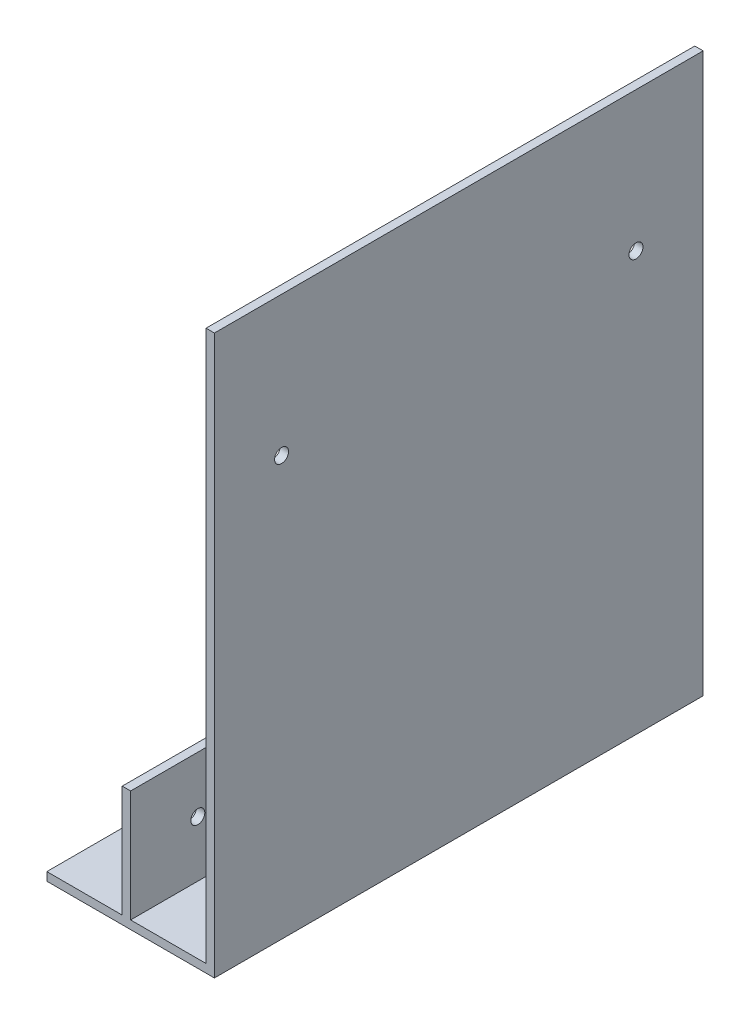
SolidWorks part; units mm, degrees
ref_plane "Front Plane" through (0, 0, 0) normal (0, 0, 1) x (1, 0, 0)
ref_plane "Top Plane" through (0, 0, 0) normal (0, 1, 0) x (1, 0, 0)
ref_plane "Right Plane" through (0, 0, 0) normal (1, 0, 0) x (0, 0, -1)
sketch "Sketch1" plane through (0, 0, 0) normal (0, 0, 1) x (1, 0, 0)
  line L0 (3, 58.977) -> (3, -21.023)
  line L1 (3, -21.023) -> (57, -21.023)
  line L3 (3, 58.977) -> (-3, 58.977)
  line L4 (57, -27.023) -> (-57, -27.023)
  line L5 (0, 78.1564) -> (0, -121.8463) construction
  line L6 (-57, -21.023) -> (-57, -27.023)
  line L7 (-3, -21.023) -> (-57, -21.023)
  line L8 (-3, 58.977) -> (-3, -21.023)
  line L9 (57, -21.023) -> (57, 372.977)
  line L10 (57, 372.977) -> (63, 372.977)
  line L11 (63, 372.977) -> (63, -27.023)
  line L12 (57, -27.023) -> (63, -27.023)
  point P10 (0, 58.977)
  point P11 (0, -27.023)
  dimension "D1" = 80
  dimension "D2" = 6
  dimension "D3" = 3
  dimension "D4" = 54
  dimension "D5" = 400
  dimension "D6" = 6
extrude "Boss-Extrude1" add sketch "Sketch1" along normal blind 350
sketch "Sketch2" plane through (0, -21.023, 0) normal (0, 1, 0) x (1, 0, 0)
  line L0 (-30, 0) -> (-30, -350) construction
  line L1 (-3, 0) -> (-57, 0) construction
  line L2 (-3, -350) -> (-57, -350) construction
  line L3 (-57, -175) -> (-3, -175) construction
  line L4 (-57, -350) -> (-57, 0) construction
  line L5 (-3, -350) -> (-3, 0) construction
  line L6 (0, 0) -> (0, -350) construction
  line L7 (3, -350) -> (-3, -350) construction
  circle A0 centre (-30, -150) radius 3
  circle A1 centre (-30, -200) radius 3
  circle A2 centre (30, -200) radius 3
  circle A3 centre (30, -150) radius 3
  dimension "D1" = 25
extrude "Cut-Extrude1" cut sketch "Sketch2" along normal through all and the other way through all
sketch "Sketch3" plane through (3, 0, 0) normal (1, 0, 0) x (0, 0, -1)
  line L0 (-175, 58.977) -> (-175, -21.023) construction
  line L1 (-350, 58.977) -> (0, 58.977) construction
  line L2 (-350, -21.023) -> (0, -21.023) construction
  line L3 (-350, 18.977) -> (0, 18.977) construction
  line L4 (-350, -21.023) -> (-350, 58.977) construction
  line L5 (0, -21.023) -> (0, 58.977) construction
  circle A0 centre (-175, 18.977) radius 11
  circle A1 centre (-301.8959, 18.977) radius 5
  circle A2 centre (-48.1041, 18.977) radius 5
  point P18 (0, 0)
  point P19 (0, 0)
  dimension "D1" = 22
extrude "Cut-Extrude2" cut sketch "Sketch3" against normal through all
sketch "Sketch4" plane through (57, 0, 0) normal (-1, 0, 0) x (0, 0, 1)
  line L0 (175, 372.977) -> (175, -21.023) construction
  line L1 (350, 372.977) -> (0, 372.977) construction
  line L2 (350, -21.023) -> (0, -21.023) construction
  line L3 (0, 272.977) -> (350, 272.977) construction
  line L4 (0, 372.977) -> (0, -21.023) construction
  line L5 (350, 372.977) -> (350, -21.023) construction
  circle A0 centre (48.1, 272.977) radius 5
  circle A1 centre (301.9, 272.977) radius 5
  dimension "D2" = 126.9
  dimension "D1" = 100
extrude "Cut-Extrude3" cut sketch "Sketch4" against normal through all
